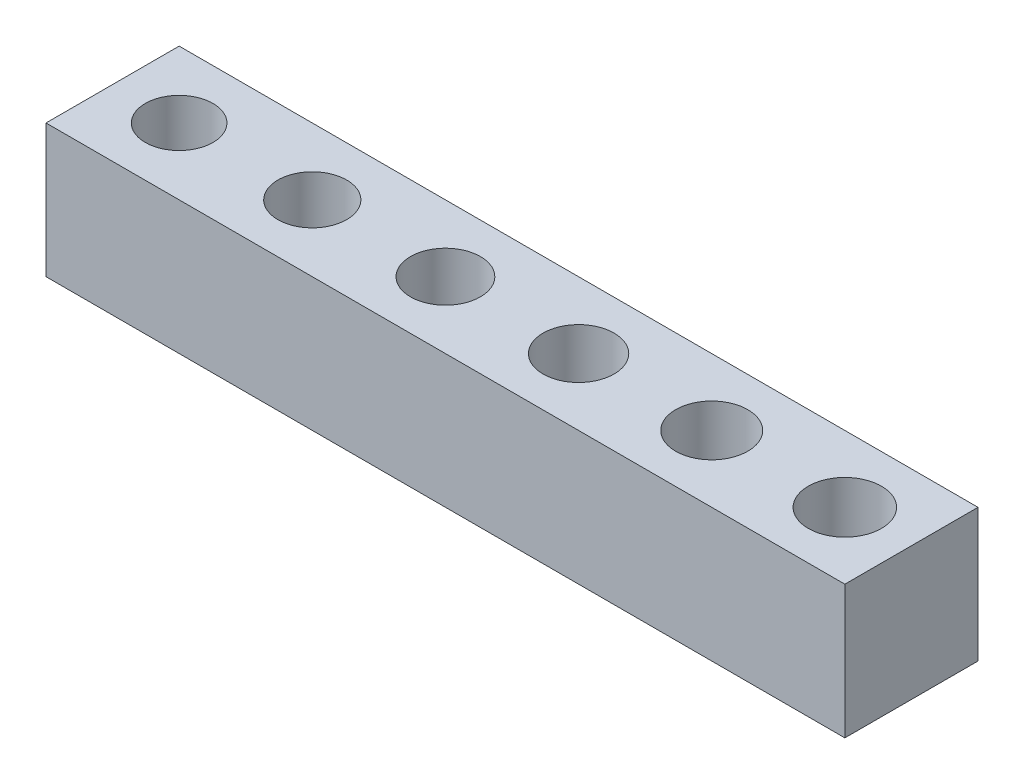
SolidWorks part; units mm, degrees
ref_plane "Front Plane" through (0, 0, 0) normal (0, 0, 1) x (1, 0, 0)
ref_plane "Top Plane" through (0, 0, 0) normal (0, 1, 0) x (1, 0, 0)
ref_plane "Right Plane" through (0, 0, 0) normal (1, 0, 0) x (0, 0, -1)
sketch "Sketch1" plane through (0, 0, 0) normal (0, 1, 0) x (1, 0, 0)
  line L0 (0, 0) -> (12, 12) construction
  line L1 (0, 0) -> (12, 0)
  line L2 (0, 0) -> (0, 12)
  line L3 (0, 12) -> (12, 12)
  line L4 (12, 0) -> (12, 12)
  circle A0 centre (6, 6) radius 2.475
  point P5 (6, 6)
  dimension "D2" = 4.95
  dimension "D1" = 12
extrude "Boss-Extrude1" add sketch "Sketch1" along normal blind 12
pattern_linear "LPattern1" count 5 spacing 12 along (-1, 0, 0) count 2 spacing 12 along (1, 0, 0) of "Boss-Extrude1"
sketch "Sketch2" plane through (0, 12, 0) normal (0, 1, 0) x (1, 0, 0)
  circle A0 centre (-42, 6) radius 3.05
  circle A1 centre (-30, 6) radius 3.1
  circle A2 centre (-18, 6) radius 3.15
  circle A3 centre (-6, 6) radius 3.2
  circle A4 centre (6, 6) radius 3.25
  circle A5 centre (18, 6) radius 3.3
  dimension "D1" = 6.1
  dimension "D2" = 6.2
  dimension "D3" = 6.3
  dimension "D4" = 6.4
  dimension "D5" = 6.5
  dimension "D6" = 6.6
extrude "Cut-Extrude1" cut sketch "Sketch2" against normal blind 5.75
